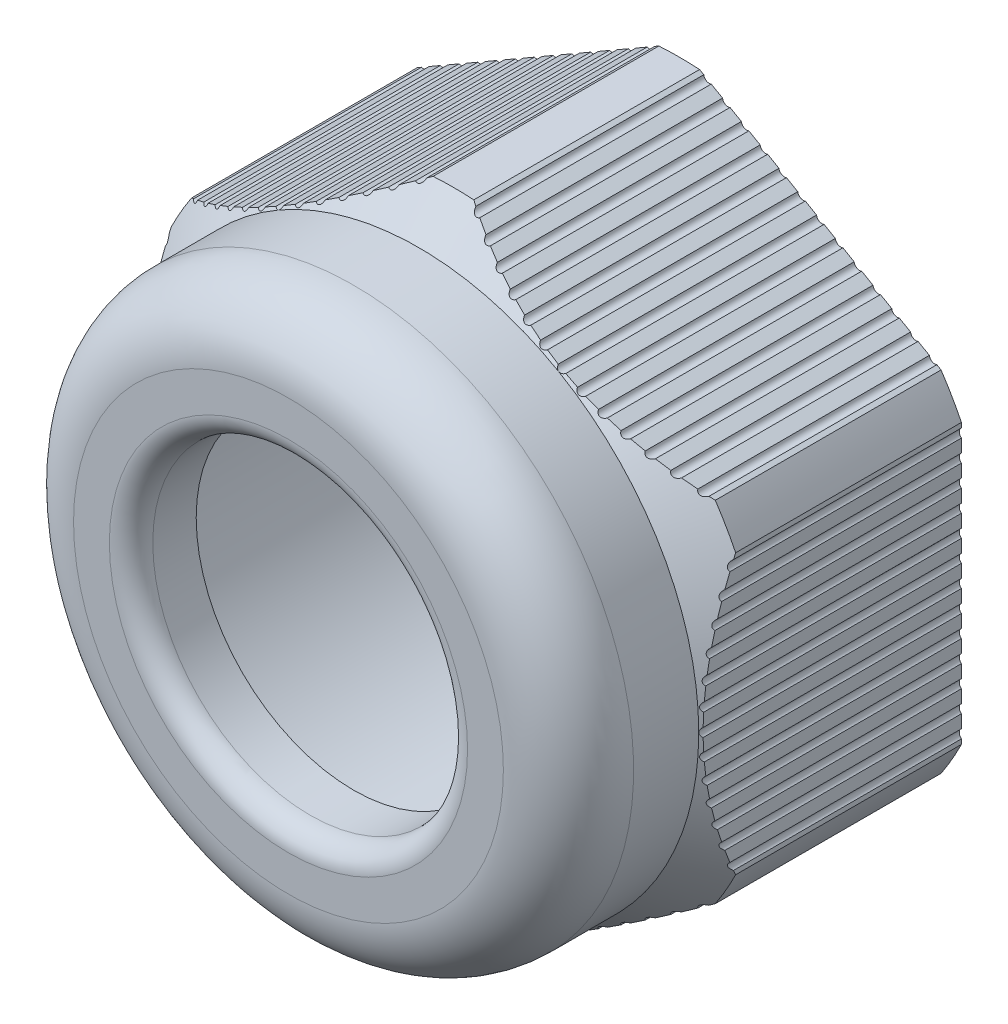
SolidWorks part; units mm, degrees
ref_plane "Спереди" through (0, 0, 0) normal (0, 0, 1) x (1, 0, 0)
ref_plane "Сверху" through (0, 0, 0) normal (0, 1, 0) x (1, 0, 0)
ref_plane "Справа" through (0, 0, 0) normal (1, 0, 0) x (0, 0, -1)
sketch "Эскиз2" plane through (0, 0, 0) normal (0, 0, 1) x (1, 0, 0)
  line L0 (0, 15.0111) -> (0, -15.0111) construction
  line L1 (0, 15.0111) -> (-13, 7.5056)
  line L2 (-13, 7.5056) -> (-13, -7.5056)
  line L3 (-13, -7.5056) -> (0, -15.0111)
  line L4 (0, -15.0111) -> (13, -7.5056)
  line L5 (13, -7.5056) -> (13, 7.5056)
  line L6 (13, 7.5056) -> (0, 15.0111)
  circle A0 centre (0, 0) radius 15.0111
  dimension "D1" = 120
  dimension "D2" = 120
  dimension "D3" = 26
extrude "Вытянуть1" add sketch "Эскиз2" along normal blind 12 contours L1 L2 L3 L4 L5 L6
sketch "Эскиз3" plane through (0, 0, 12) normal (0, 0, 1) x (1, 0, 0)
  circle A0 centre (0, 0) radius 14.5
  circle A1 centre (0, 0) radius 15.0111
  dimension "D1" = 29
extrude "Вырез-Вытянуть1" cut sketch "Эскиз3" against normal blind 12
sketch "Эскиз4" plane through (0, 0, 12) normal (0, 0, 1) x (1, 0, 0)
  circle A0 centre (0, 0) radius 12.9
  dimension "D1" = 25.8
extrude "Вытянуть3" add sketch "Эскиз4" along normal offset from surface (6 mm away) 18 up to face at (0, 0, 0)
fillet "Скругление1" radius 3 1 edges at (-12.9, 0, 18)
sketch "Эскиз5" plane through (0, 0, 18) normal (0, 0, 1) x (1, 0, 0)
  circle A0 centre (0, 0) radius 7.25
  dimension "D1" = 14.5
extrude "Вырез-Вытянуть2" cut sketch "Эскиз5" against normal through all
sketch "Эскиз6" plane through (0, 0, 0) normal (0, 0, -1) x (-1, 0, 0)
  circle A0 centre (0, 0) radius 10.75
  dimension "D1" = 21.5
extrude "Вырез-Вытянуть3" cut sketch "Эскиз6" against normal offset from surface (15 mm away) 3 up to face at (7.25, 0, 18)
fillet "Скругление2" radius 1 1 edges at (7.25, 0, 18)
chamfer "Фаска1" distance 2 angle 60 1 edges at (-10.75, 0, 15)
ref_axis "Ось1" through (0, 0, 27.1651) along (0, 0, -1)
sketch "Эскиз7" plane through (0, 0, 0) normal (1, 0, 0) x (0, 0, -1)
  line L0 (-12, 12.9) -> (-10, 14.9)
  line L1 (-10, 14.9) -> (-12, 14.9)
  line L2 (-12, 14.9) -> (-12, 12.9)
  dimension "D1" = 2
  dimension "D2" = 45
revolve "Вырез-Повернуть1" cut sketch "Эскиз7" angle 360 about axis through (0, 0, 27.1651) along (0, 0, -1)
sketch "Эскиз8" plane through (0, 0, 0) normal (0, 0, -1) x (-1, 0, 0)
  line L0 (-6.5, 11.2583) -> (-6.575, 11.3882) construction
  line L1 (-12.0621, 8.047) -> (-0.9379, 14.4696) construction
  line L2 (-6.5, 11.2583) -> (-6.45, 11.1717) construction
  circle A0 centre (-6.575, 11.3882) radius 0.25
  dimension "D1" = 0.5
  dimension "D2" = 0.15
  dimension "D3" = 0.1
extrude "Вырез-Вытянуть4" cut sketch "Эскиз8" against normal through all
pattern_linear "Линейный массив1" count 7 spacing 1 along (-0.866, 0.5, 0) count 7 spacing 1 along (0.866, -0.5, 0) of "Вырез-Вытянуть4"
pattern_circular "Круговой массив1" count 6 over 360 about axis through (0, 0, 0) along (0, 0, 1) of "Линейный массив1", "Вырез-Вытянуть4"
